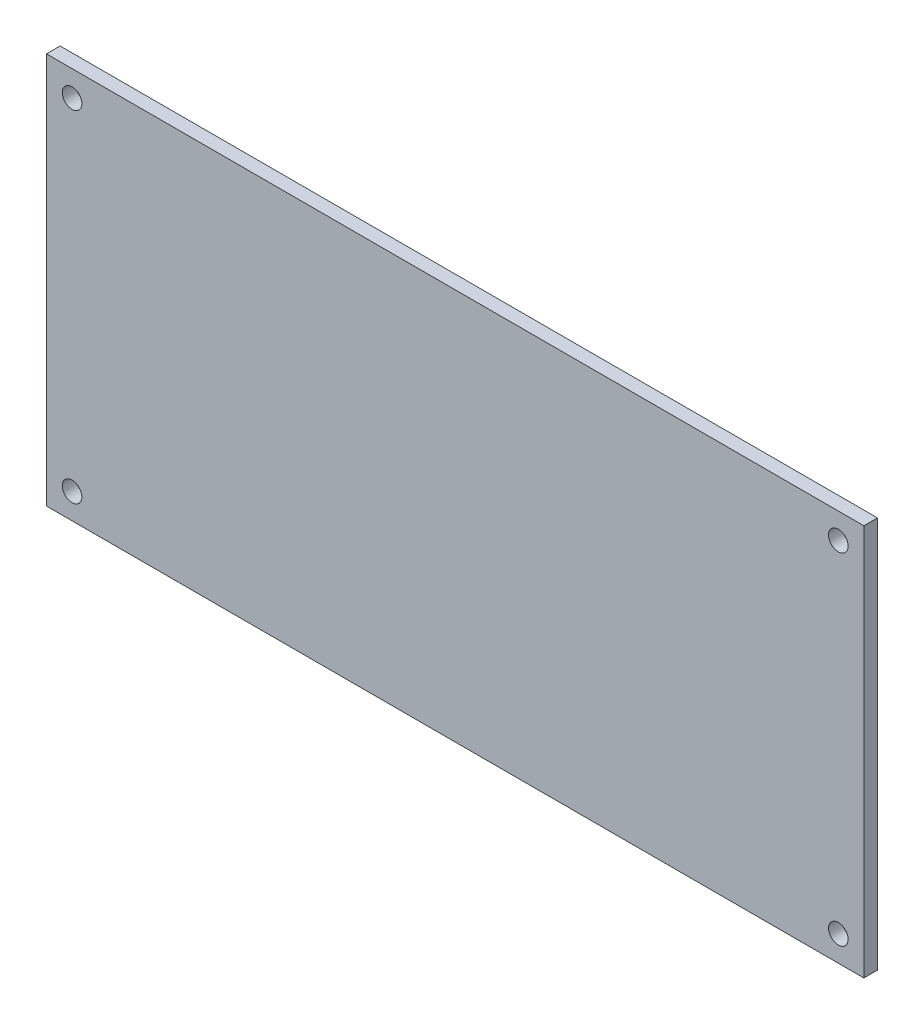
SolidWorks part; units mm, degrees
ref_plane "Plan de face" through (0, 0, 0) normal (0, 0, 1) x (1, 0, 0)
ref_plane "Plan de dessus" through (0, 0, 0) normal (0, 1, 0) x (1, 0, 0)
ref_plane "Plan de droite" through (0, 0, 0) normal (1, 0, 0) x (0, 0, -1)
sketch "Esquisse1" plane through (0, 0, 0) normal (0, 0, 1) x (1, 0, 0)
  line L0 (0, 0) -> (87.8505, 0) construction
  line L1 (-48, 23) -> (48, 23)
  line L2 (-48, 23) -> (-48, -23)
  line L3 (-48, -23) -> (48, -23)
  line L4 (48, 23) -> (48, -23)
  line L5 (0, 0) -> (0, 56.6871) construction
  circle A0 centre (-45, 20) radius 1.15
  circle A1 centre (45, 20) radius 1.15
  circle A2 centre (-45, -20) radius 1.15
  circle A3 centre (45, -20) radius 1.15
  dimension "D5" = 2.3
  dimension "D1" = 96
  dimension "D2" = 46
  dimension "D3" = 45
  dimension "D4" = 20
extrude "Boss.-Extru.1" add sketch "Esquisse1" along normal blind 1.6
